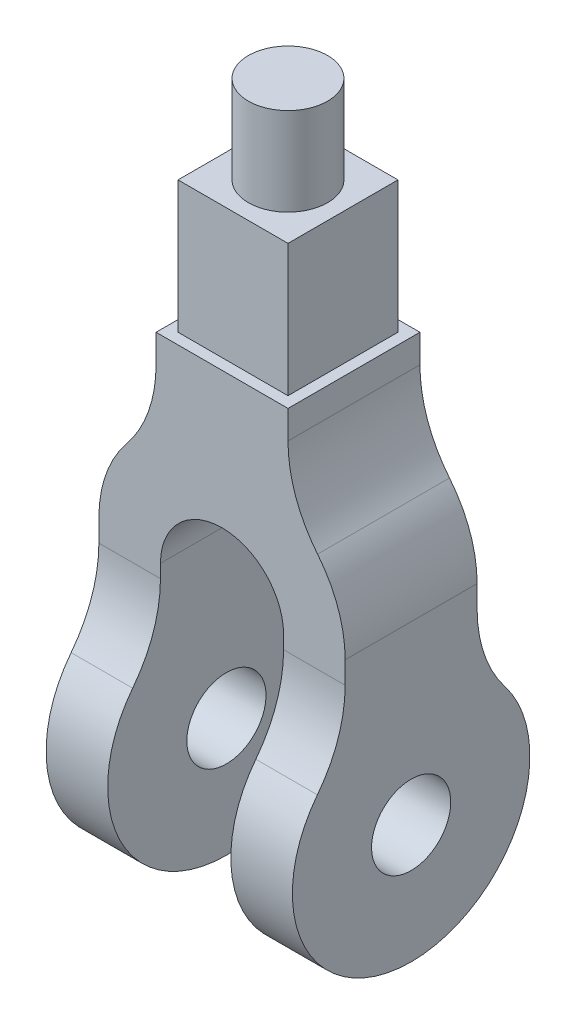
SolidWorks part; units mm, degrees
ref_plane "Front Plane" through (0, 0, 0) normal (0, 0, 1) x (1, 0, 0)
ref_plane "Top Plane" through (0, 0, 0) normal (0, 1, 0) x (1, 0, 0)
ref_plane "Right Plane" through (0, 0, 0) normal (1, 0, 0) x (0, 0, -1)
sketch "Sketch1" plane through (0, 0, 0) normal (0, 0, 1) x (1, 0, 0)
  line L1 (-65.3333, 42.6667) -> (-9.3333, 42.6667)
  line L2 (-65.3333, 42.6667) -> (-65.3333, -97.3333)
  line L3 (-65.3333, -97.3333) -> (-9.3333, -97.3333)
  line L4 (-9.3333, 42.6667) -> (-9.3333, -97.3333)
  dimension "D1" = 140
  dimension "D2" = 56
extrude "Boss-Extrude1" add sketch "Sketch1" along normal blind 54
sketch "Sketch2" plane through (0, 0, 54) normal (0, 0, 1) x (1, 0, 0)
  line L0 (-65.3333, 42.6667) -> (-65.3333, -97.3333) construction
  line L1 (-65.3333, -97.3333) -> (-9.3333, -97.3333) construction
  line L2 (-23.3333, -32.3333) -> (-23.3333, -97.3333)
  line L3 (-51.3333, -32.3333) -> (-51.3333, -97.3333)
  line L4 (-22.3333, 42.6667) -> (-22.3333, -6.6902)
  line L5 (-9.3333, 42.6667) -> (-65.3333, 42.6667) construction
  line L7 (-52.3333, 42.6667) -> (-52.3333, 6.259)
  line L8 (-37.3333, 42.6667) -> (-37.3333, -135.219) construction
  arc A0 (-23.3333, -32.3333) -> (-51.3333, -32.3333) centre (-37.3333, -32.3333) ccw
  arc A1 (-59.0575, -12.6681) -> (-51.3333, -54.582) centre (-37.3333, -30.3333) ccw
  arc A2 (-52.3333, 6.259) -> (-59.0575, -12.6681) centre (-82.3333, 6.259) cw
  dimension "D1" = 56
  dimension "D2" = 28
  dimension "D9" = 30
  dimension "D3" = 28
  dimension "D4" = 28
  dimension "D5" = 2
  dimension "D6" = 65
  dimension "D7" = 15
  dimension "D8" = 15
extrude "Cut-Extrude4" cut sketch "Sketch2" against normal blind 54
mirror "Mirror3" about plane through (-37.3333, 0, 0) normal (-1, 0, 0) of bodies 105
sketch "Sketch5" plane through (-9.3333, 0, 0) normal (1, 0, 0) x (0, 0, -1)
  line L0 (-54, -97.3333) -> (0, -97.3333) construction
  line L1 (0, -30.3333) -> (0, -97.3333) construction
  line L2 (-27, -70.3333) -> (-27, 80.1713) construction
  line L3 (0, 42.6667) -> (-54, 42.6667) construction
  line L4 (-42, 42.6667) -> (-12, 42.6667)
  line L5 (-42, 42.6667) -> (-42, -35.3476)
  line L7 (-12, 42.6667) -> (-12, -35.3476)
  arc A0 (-48.3158, -53.7612) -> (-5.6842, -53.7612) centre (-27, -70.3333) ccw
  circle A1 centre (-27, -70.3333) radius 9
  arc A2 (-48.3158, -53.7612) -> (-42, -35.3476) centre (-72, -35.3476) ccw
  arc A3 (-5.6842, -53.7612) -> (-12, -35.3476) centre (18, -35.3476) cw
  dimension "D1" = 54
  dimension "D4" = 18
  dimension "D6" = 30
  dimension "D2" = 27
  dimension "D3" = 27
  dimension "D5" = 30
extrude "Cut-Extrude6" cut sketch "Sketch5" against normal blind 60 flip side to cut
sketch "Sketch6" plane through (0, 42.6667, 0) normal (0, 1, 0) x (1, 0, 0)
  line L0 (-22.3333, -12) -> (-22.3333, -42) construction
  line L1 (-49.8333, -14.5) -> (-24.8333, -14.5)
  line L2 (-49.8333, -14.5) -> (-49.8333, -39.5)
  line L3 (-49.8333, -39.5) -> (-24.8333, -39.5)
  line L4 (-24.8333, -14.5) -> (-24.8333, -39.5)
  line L5 (-49.8333, -14.5) -> (-24.8333, -39.5) construction
  line L6 (-49.8333, -39.5) -> (-24.8333, -14.5) construction
  line L7 (-52.3333, -42) -> (-22.3333, -42) construction
  point P0 (-37.3333, -27)
  dimension "D1" = 25
  dimension "D2" = 25
  dimension "D3" = 15
  dimension "D4" = 15
extrude "Cut-Extrude7" cut sketch "Sketch6" against normal blind 30 flip side to cut
sketch "Sketch7" plane through (0, 42.6667, 0) normal (0, 1, 0) x (1, 0, 0)
  line L0 (-49.8333, -39.5) -> (-24.8333, -39.5) construction
  line L1 (-24.8333, -39.5) -> (-24.8333, -14.5) construction
  circle A0 centre (-37.3333, -27) radius 9
  dimension "D1" = 18
  dimension "D2" = 12.5
  dimension "D3" = 12.5
extrude "Boss-Extrude2" add sketch "Sketch7" along normal blind 20
